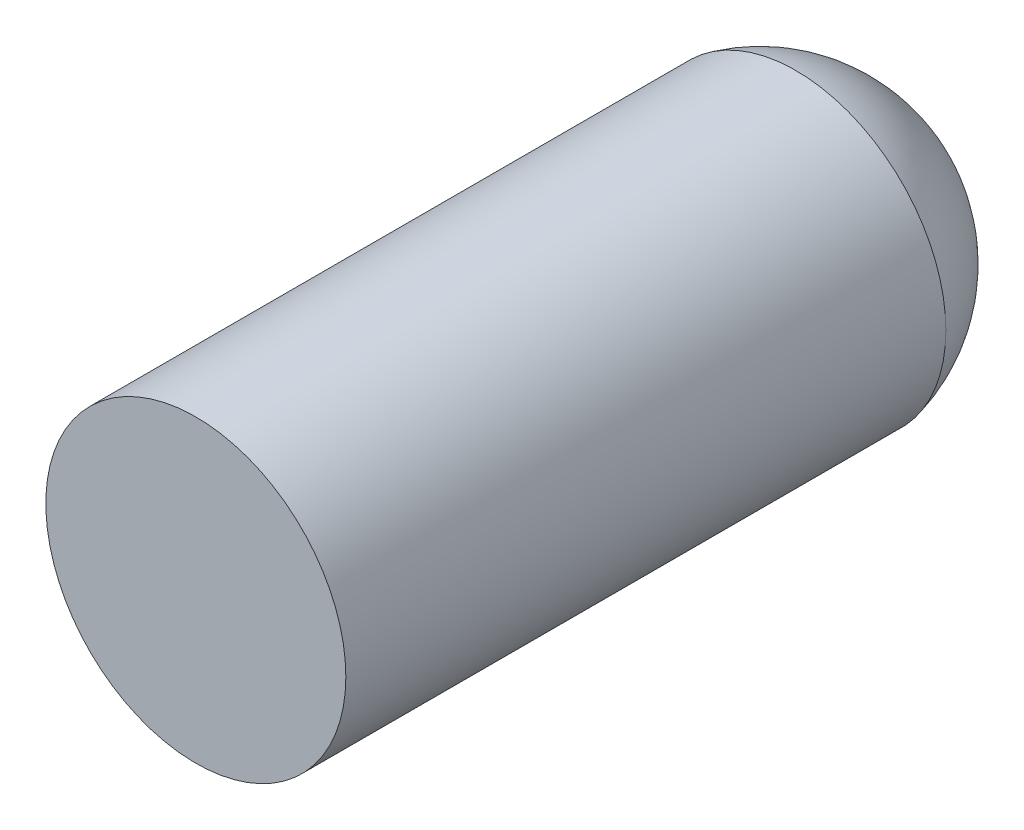
SolidWorks part; units mm, degrees
ref_plane "Front" through (0, 0, 0) normal (0, 0, 1) x (1, 0, 0)
ref_plane "Top" through (0, 0, 0) normal (0, 1, 0) x (1, 0, 0)
ref_plane "Right" through (0, 0, 0) normal (1, 0, 0) x (0, 0, -1)
sketch "Sketch2" plane through (0, 0, 0) normal (0, 0, 1) x (1, 0, 0)
  circle A0 centre (0, 0) radius 6.35
  dimension "D1" = 12.7
extrude "Boss-Extrude1" add sketch "Sketch2" along normal blind 25.4
sketch "Sketch7" plane through (0, 0, 0) normal (0, 1, 0) x (1, 0, 0)
  line L0 (0, 0) -> (0, 5.0129)
  line L1 (0, 0) -> (6.35, 0)
  arc A0 (0, 5.0129) -> (6.35, 0) centre (0, -1.5154) cw
revolve "Revolve1" add sketch "Sketch7" angle 360 about L0
